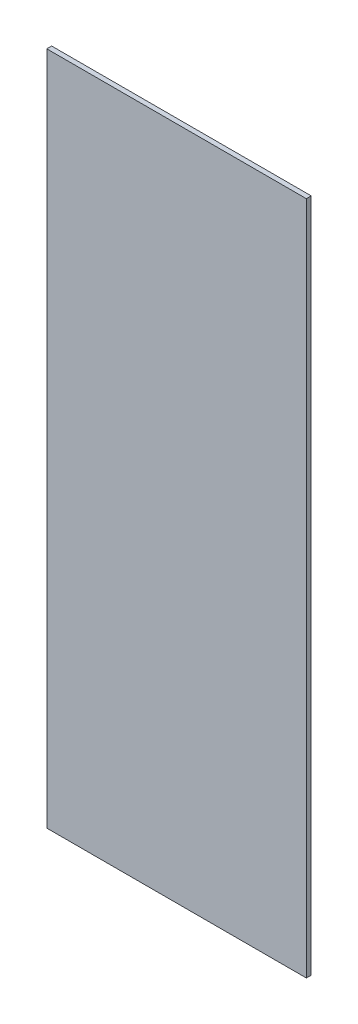
SolidWorks part; units mm, degrees
ref_plane "Plan de face" through (0, 0, 0) normal (0, 0, 1) x (1, 0, 0)
ref_plane "Plan de dessus" through (0, 0, 0) normal (0, 1, 0) x (1, 0, 0)
ref_plane "Plan de droite" through (0, 0, 0) normal (1, 0, 0) x (0, 0, -1)
sketch "Esquisse1" plane through (0, 0, 0) normal (0, 0, 1) x (1, 0, 0)
  line L1 (-160, -416) -> (160, -416)
  line L2 (-160, -416) -> (-160, 416)
  line L3 (-160, 416) -> (160, 416)
  line L4 (160, -416) -> (160, 416)
  line L5 (-160, -416) -> (160, 416) construction
  line L6 (-160, 416) -> (160, -416) construction
  point P0 (0, 0)
  dimension "D1" = 320
  dimension "D2" = 832
extrude "Boss.-Extru.1" add sketch "Esquisse1" along normal blind 6
